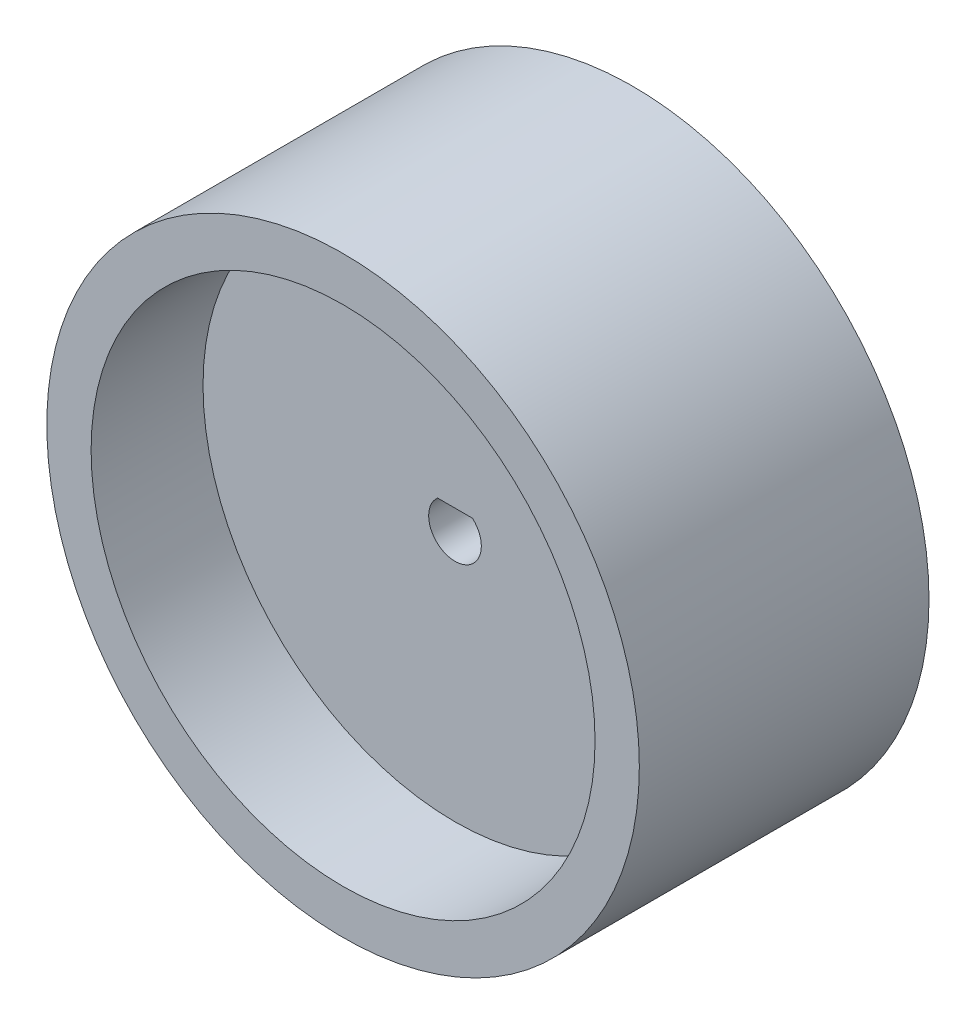
SolidWorks part; units mm, degrees
ref_plane "Front Plane" through (0, 0, 0) normal (0, 0, 1) x (1, 0, 0)
ref_plane "Top Plane" through (0, 0, 0) normal (0, 1, 0) x (1, 0, 0)
ref_plane "Right Plane" through (0, 0, 0) normal (1, 0, 0) x (0, 0, -1)
sketch "Sketch1" plane through (0, 0, 1381.117) normal (0, 0, 1) x (1, 0, 0)
  line L0 (621.3667, 902.5723) -> (624.0125, 902.5723)
  circle A0 centre (622.6896, 901.0723) radius 5
  arc A1 (621.3667, 902.5723) -> (624.0125, 902.5723) centre (622.6896, 901.0723) ccw
  dimension "D1" = 10
extrude "Boss-Extrude2" add sketch "Sketch1" along normal blind 13.5
ref_plane "Plane1" through (0, 0, 1392.117) normal (0, 0, 1) x (1, 0, 0)
sketch "Sketch3" plane through (0, 0, 1392.117) normal (0, 0, 1) x (1, 0, 0)
  circle A0 centre (622.6896, 901.0723) radius 22.5
  circle A1 centre (622.6896, 901.0723) radius 19.1367
  dimension "D1" = 45
extrude "Boss-Extrude3" add sketch "Sketch3" along normal mid plane 22 separate body
sketch "Sketch4" plane through (0, 0, 1392.117) normal (0, 0, 1) x (1, 0, 0)
  circle A0 centre (622.6896, 901.0723) radius 20
  circle A1 centre (622.6896, 901.0723) radius 4.2934
  dimension "D1" = 40
extrude "Boss-Extrude4" add sketch "Sketch4" along normal mid plane 5
